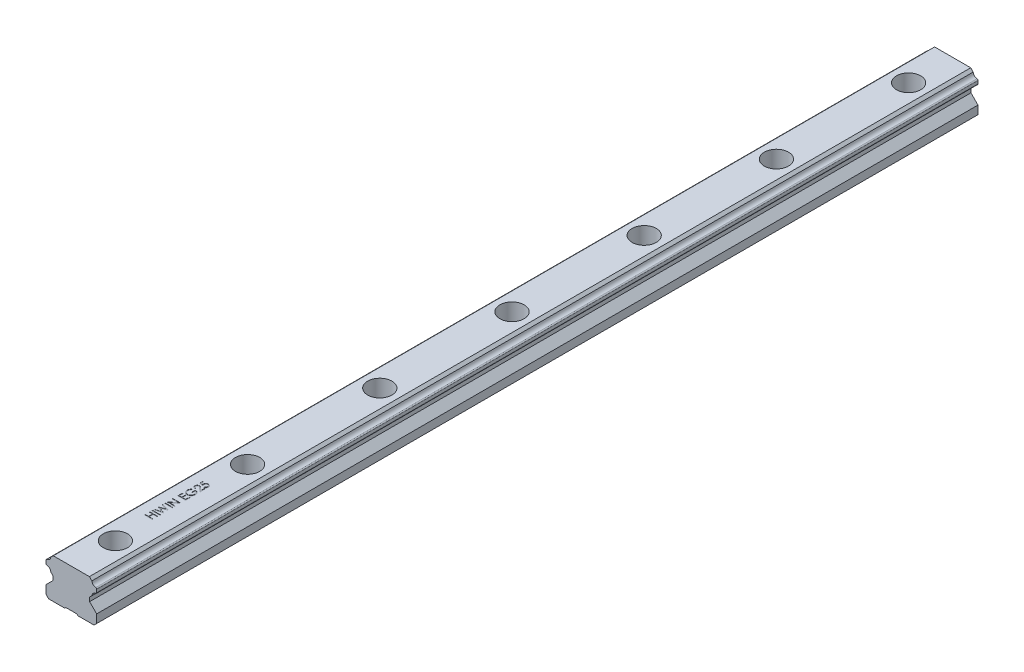
SolidWorks part; units mm, degrees
material "镀铬不锈钢"
ref_plane "前视基准面" through (0, 0, 0) normal (0, 0, 1) x (1, 0, 0)
ref_plane "上视基准面" through (0, 0, 0) normal (0, 1, 0) x (1, 0, 0)
ref_plane "右视基准面" through (0, 0, 0) normal (1, 0, 0) x (0, 0, -1)
sketch "草图1" plane through (0, 0, 0) normal (0, 0, 1) x (1, 0, 0)
  line L22 (-8.3, 10) -> (-8.3, 8.2)
  line L23 (-10.3, 0) -> (-3, 0)
  line L24 (-3, 0) -> (-2.5, 0.5)
  line L25 (2.5, 0.5) -> (3, 0)
  line L26 (3, 0) -> (10.3, 0)
  line L27 (11.5, 1.2) -> (11.5, 5)
  line L28 (11.5, 5) -> (8.3, 8.2)
  line L29 (-2.5, 0.5) -> (2.5, 0.5)
  line L30 (-8.3, 8.2) -> (-11.5, 5)
  line L31 (10.3, 0) -> (11.5, 1.2)
  line L32 (-11.5, 1.2) -> (-10.3, 0)
  line L33 (-8.196, 18) -> (-9.3139, 16.8821)
  line L34 (-9.305, 11.005) -> (-8.3, 10)
  line L35 (-11.5, 5) -> (-11.5, 1.2)
  line L36 (8.3, 8.2) -> (8.3, 10)
  line L37 (8.196, 18) -> (-8.196, 18)
  line L38 (8.3, 10) -> (9.305, 11.005)
  line L39 (0, 0) -> (0, 18) construction
  line L40 (-3, 0) -> (3, 0) construction
  line L41 (11.5, 13.346) -> (11.5, 14.6354)
  line L42 (9.3139, 16.8821) -> (8.196, 18)
  line L43 (-11.5, 14.6354) -> (-11.5, 13.346)
  arc A8 (11.5, 14.6354) -> (11.06, 15.1318) centre (11, 14.6354) ccw
  arc A9 (-11.06, 15.1318) -> (-9.3139, 16.8821) centre (-11.3, 17.1173) ccw
  arc A10 (-11.5, 13.346) -> (-11.06, 12.8496) centre (-11, 13.346) ccw
  arc A11 (9.3139, 16.8821) -> (11.06, 15.1318) centre (11.3, 17.1173) ccw
  arc A12 (11.06, 12.8496) -> (11.5, 13.346) centre (11, 13.346) ccw
  arc A13 (11.06, 12.8496) -> (9.305, 11.005) centre (11.3, 10.864) ccw
  arc A14 (-11.06, 15.1318) -> (-11.5, 14.6354) centre (-11, 14.6354) ccw
  arc A15 (-9.305, 11.005) -> (-11.06, 12.8496) centre (-11.3, 10.864) ccw
extrude "凸台-拉伸1" add sketch "草图1" against normal blind 400
hole_wizard "M6 六角凹头螺钉的柱形沉头孔1" positions "草图3" profile "草图2" counterbore size "M6" standard "ISO" end condition through all
sketch "草图3" plane through (0.3202, 18, -29.2297) normal (0, 1, 0) x (-1, 0, 0)
  point P0 (0.3202, 9.2297)
  dimension "D1" = 20
sketch "草图2" plane through (0, 18, -20) normal (1, 0, 0) x (0, 0, 1)
  line L0 (0, 0) -> (0, 18)
  line L1 (0, 18) -> (3.5, 18)
  line L3 (3.5, 18) -> (3.5, 9)
  line L4 (3.5, 9) -> (5.5, 9)
  line L5 (5.5, 9) -> (5.5, 0)
  line L7 (5.5, 0) -> (0, 0)
  line L11 (0, -6.35) -> (0, 107.95) construction
  dimension "通孔孔直径" = 7
  dimension "通孔孔深度" = 18
  dimension "柱形沉头孔直径" = 11
  dimension "柱形沉头孔深度" = 9
pattern_linear "阵列(线性)1" count 7 spacing 60 along (0, 0, -1) of "M6 六角凹头螺钉的柱形沉头孔1"
sketch "草图6" plane through (0, 18, 0) normal (0, 1, 0) x (1, 0, 0)
  line L0 (0, 20) -> (0, 80) construction
  text T0 "HIWIN EG25"
extrude "切除-拉伸1" cut sketch "草图6" against normal blind 0.1
equation "\"D1@凸台-拉伸1\" = 2 * \"D1@草图3\" + \"D3@阵列(线性)1\" *  ( \"D1@阵列(线性)1\"  - 1) "
